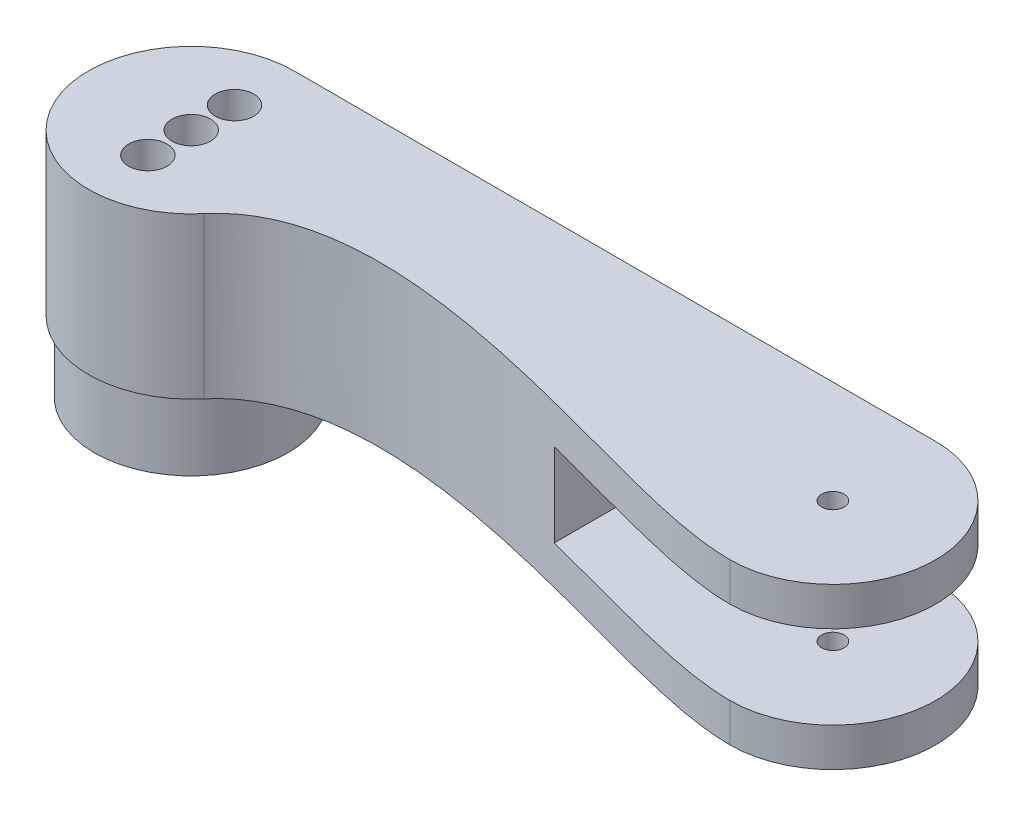
SolidWorks part; units mm, degrees
ref_plane "Front Plane" through (0, 0, 0) normal (0, 0, 1) x (1, 0, 0)
ref_plane "Top Plane" through (0, 0, 0) normal (0, 1, 0) x (1, 0, 0)
ref_plane "Right Plane" through (0, 0, 0) normal (1, 0, 0) x (0, 0, -1)
sketch "Sketch1" plane through (0, 0, 0) normal (0, 1, 0) x (1, 0, 0)
  line L0 (-50, 0) -> (50, 0) construction
  line L1 (-50, 16) -> (50, 16)
  line L2 (-50, -16) -> (50, -16)
  arc A0 (-50, 16) -> (-50, -16) centre (-50, 0) ccw
  arc A1 (50, -16) -> (50, 16) centre (50, 0) ccw
  point P3 (0, 0)
  dimension "D1" = 16
  dimension "D2" = 100
extrude "Boss-Extrude1" add sketch "Sketch1" along normal blind 6
sketch "Sketch3" plane through (0, 0, 0) normal (0, -1, 0) x (1, 0, 0)
  circle A0 centre (50, 0) radius 1.75
  dimension "D1" = 3.5
extrude "Cut-Extrude2" cut sketch "Sketch3" against normal through all
sketch "Sketch4" plane through (0, 6, 0) normal (0, 1, 0) x (1, 0, 0)
  line L0 (-50, 16) -> (15, 16)
  line L1 (-50, 16) -> (50, 16) construction
  line L2 (15, 16) -> (15, -16)
  line L3 (-50, -16) -> (50, -16) construction
  line L4 (15, -16) -> (-50, -16)
  arc A0 (-50, 16) -> (-50, -16) centre (-50, 0) ccw
  arc A1 (-50, 16) -> (-50, -16) centre (-50, 0) ccw construction
  dimension "D1" = 65
extrude "Boss-Extrude2" add sketch "Sketch4" along normal blind 13
sketch "Sketch5" plane through (0, 19, 0) normal (0, 1, 0) x (1, 0, 0)
  line L0 (-50, 0) -> (50, 0) construction
  line L1 (-50, 16) -> (50, 16)
  line L2 (-50, -16) -> (50, -16)
  arc A0 (-50, 16) -> (-50, -16) centre (-50, 0) ccw
  arc A1 (50, -16) -> (50, 16) centre (50, 0) ccw
  point P4 (0, 0)
  dimension "D1" = 16
extrude "Boss-Extrude3" add sketch "Sketch5" along normal blind 6
sketch "Sketch6" plane through (0, 25, 0) normal (0, 1, 0) x (1, 0, 0)
  circle A0 centre (50, 0) radius 1.75
  dimension "D1" = 3.5
extrude "Cut-Extrude3" cut sketch "Sketch6" against normal up to next
sketch "Sketch7" plane through (0, 25, 0) normal (0, 1, 0) x (1, 0, 0)
  line L0 (0, -10.45) -> (0, 10.45) construction
  line L1 (-50, -16) -> (50, -16)
  circle A0 centre (-50, 0) radius 16
  circle A1 centre (50, 0) radius 16
  spline S0 degree 3 poles (-37.7313, -10.2703) (-30.3326, -1.4318) (6.0504, -3.3646) (38.5122, -16) (50, -16) knots 0 0 0 0 0.426661 1 1 1 1
  line M5 (-50, -16) -> (50, -16)
extrude "Cut-Extrude4" cut sketch "Sketch7" against normal up to next contours S0 A0 M5
sketch "Sketch8" plane through (0, 0, 0) normal (0, -1, 0) x (1, 0, 0)
  circle A1 centre (-50, 0) radius 15.1
  dimension "D1" = 30.2
extrude "Boss-Extrude4" add sketch "Sketch8" along normal blind 11
sketch "Sketch9" plane through (0, -11, 0) normal (0, -1, 0) x (1, 0, 0)
  circle A0 centre (-50, 0) radius 6.75 construction
  circle A1 centre (-50, 6.75) radius 1.75
  circle A2 centre (-50, -6.75) radius 1.75
  arc A3 (-50, 16) -> (-50, -16) centre (-50, 0) ccw construction
  point P6 (-50, 0)
  dimension "D1" = 13.5
  dimension "D2" = 3.5
extrude "Cut-Extrude5" cut sketch "Sketch9" against normal blind 10
sketch "Sketch11" plane through (0, -11, 0) normal (0, -1, 0) x (1, 0, 0)
  circle A0 centre (-50, 0) radius 3
  dimension "D1" = 6
extrude "Cut-Extrude6" cut sketch "Sketch11" against normal up to next and the other way through all
sketch "Sketch12" plane through (0, -1, 0) normal (0, -1, 0) x (1, 0, 0)
  circle A0 centre (-50, 0) radius 6.75 construction
  circle A1 centre (-50, 6.75) radius 3
  circle A2 centre (-50, -6.75) radius 3
  circle A3 centre (-50, 6.75) radius 1.75 construction
  dimension "D1" = 6
  dimension "D3" = 13.5
  dimension "D2" = 2
extrude "Cut-Extrude7" cut sketch "Sketch12" against normal up to next
equation "\"Length\"= 100mm"
equation "\"Radius\"= 14.25mm"
equation "\"Thick\"= 12mm"
equation "\"D1@Sketch1\"=16"
equation "\"D2@Sketch1\" = \"Length\""
equation "\"D1@Boss-Extrude1\"= \"Thick\""
equation "\"D1@Sketch4\"=\"Length\"*0.65"
equation "\"D1@Sketch5\"=16"
equation "\"D1@Boss-Extrude4\"=\"Thick\"-1"
